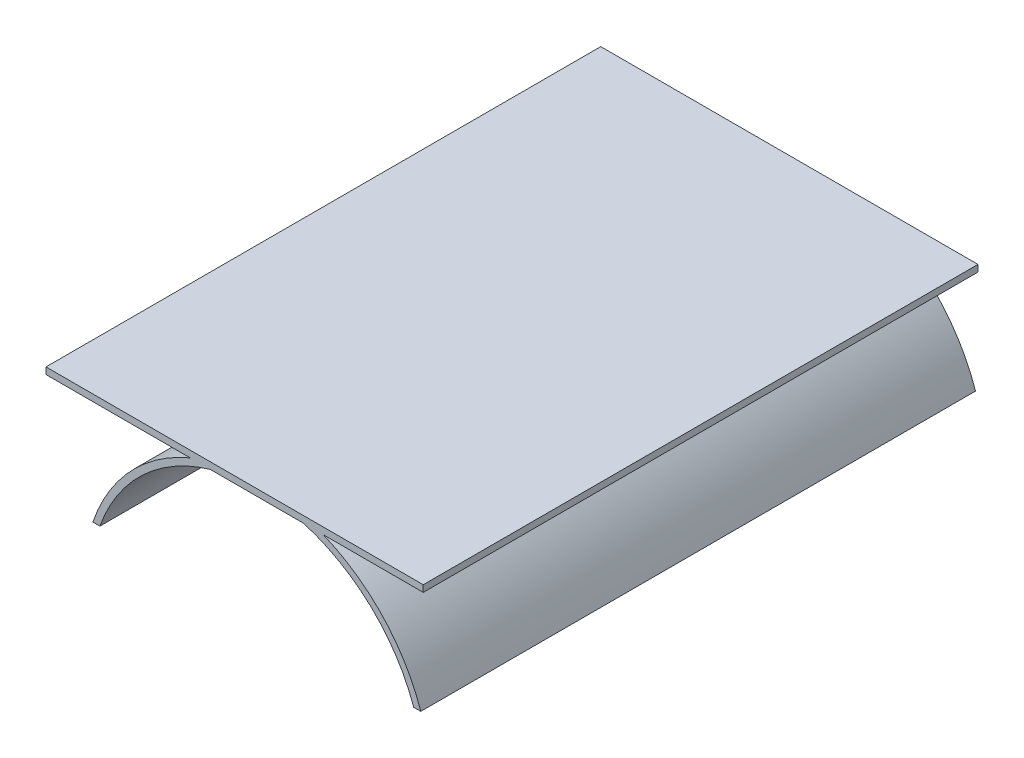
SolidWorks part; units mm, degrees
ref_plane "Plan de face" through (0, 0, 0) normal (0, 0, 1) x (1, 0, 0)
ref_plane "Plan de dessus" through (0, 0, 0) normal (0, 1, 0) x (1, 0, 0)
ref_plane "Plan de droite" through (0, 0, 0) normal (1, 0, 0) x (0, 0, -1)
sketch "Esquisse1" plane through (0, 0, 0) normal (0, 0, 1) x (1, 0, 0)
  line L1 (0, 0) -> (170, 0)
  line L2 (0, 0) -> (0, 3)
  line L3 (0, 3) -> (170, 3)
  line L4 (170, 0) -> (170, 3)
  dimension "D1" = 170
  dimension "D2" = 3
extrude "Boss.-Extru.1" add sketch "Esquisse1" along normal blind 250
sketch "Esquisse3" plane through (0, 0, 250) normal (0, 0, 1) x (1, 0, 0)
  line L0 (170, 3) -> (0, 3) construction
  line L1 (170, 0) -> (170, 3) construction
  line L2 (21.115, -47) -> (24.2893, -47)
  line L3 (165.7107, -47) -> (168.885, -47)
  line L4 (65, 0) -> (74, 0)
  line L5 (0, 3) -> (170, 3)
  line L6 (0, 3) -> (0, 0)
  line L7 (0, 0) -> (170, 0)
  line L8 (170, 3) -> (170, 0)
  line L9 (116, 0) -> (125, 0)
  arc A0 (165.7107, -47) -> (116, 0) centre (95, -72) ccw
  arc A1 (168.885, -47) -> (125, 0) centre (95, -72) ccw
  arc A2 (65, 0) -> (21.115, -47) centre (95, -72) ccw
  circle A3 centre (95, -72) radius 75 construction
  circle A4 centre (95, -72) radius 78 construction
  arc A5 (74, 0) -> (24.2893, -47) centre (95, -72) ccw
  point P1 (173, -72)
  point P10 (166.7229, -50.0721)
  dimension "D1" = 150
  dimension "D2" = 75
  dimension "D3" = 75
  dimension "D5" = 25
  dimension "D4" = 3
extrude "Boss.-Extru.2" add sketch "Esquisse3" against normal blind 250 contours A0 L9 A1 L3 | A5 L2 A2 L4
